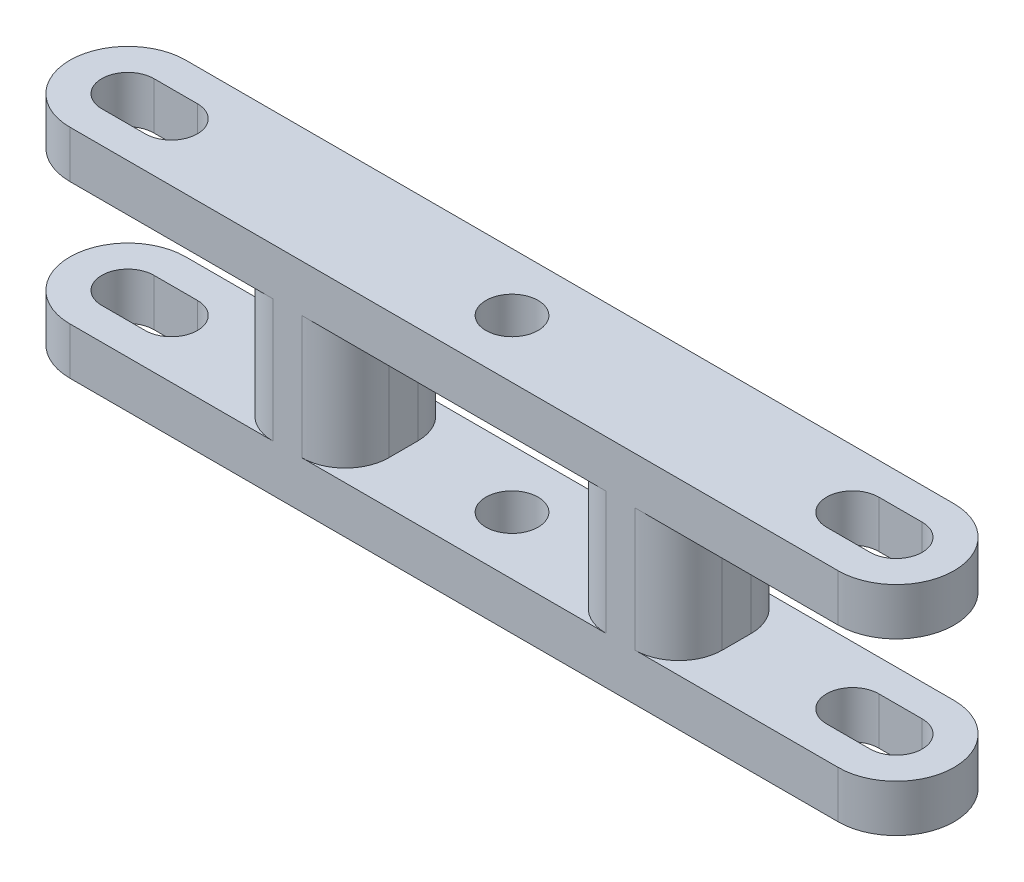
SolidWorks part; units mm, degrees
ref_plane "Front Plane" through (0, 0, 0) normal (0, 0, 1) x (1, 0, 0)
ref_plane "Top Plane" through (0, 0, 0) normal (0, 1, 0) x (1, 0, 0)
ref_plane "Right Plane" through (0, 0, 0) normal (1, 0, 0) x (0, 0, -1)
sketch "Sketch1" plane through (0, 0, 0) normal (0, 1, 0) x (1, 0, 0)
  line L0 (33.655, 0) -> (-33.655, 0) construction
  line L1 (-33.655, 0) -> (-29.845, 0) construction
  line L2 (33.655, -5.08) -> (-33.655, -5.08)
  line L3 (33.655, 5.08) -> (-33.655, 5.08)
  line L6 (33.655, 0) -> (29.845, 0) construction
  line L7 (33.655, -2.286) -> (29.845, -2.286)
  line L8 (33.655, 2.286) -> (29.845, 2.286)
  line L9 (-33.655, 2.286) -> (-29.845, 2.286)
  line L10 (-33.655, -2.286) -> (-29.845, -2.286)
  arc A0 (33.655, -5.08) -> (33.655, 5.08) centre (33.655, 0) ccw
  arc A1 (-33.655, 5.08) -> (-33.655, -5.08) centre (-33.655, 0) ccw
  arc A6 (33.655, -2.286) -> (33.655, 2.286) centre (33.655, 0) ccw
  arc A7 (29.845, 2.286) -> (29.845, -2.286) centre (29.845, 0) ccw
  circle A8 centre (0, 0) radius 2.286
  arc A9 (-33.655, 2.286) -> (-33.655, -2.286) centre (-33.655, 0) ccw
  arc A10 (-29.845, -2.286) -> (-29.845, 2.286) centre (-29.845, 0) ccw
  point P5 (0, 0)
  point P12 (-31.75, 0)
  point P19 (31.75, 0)
  dimension "D5" = 4.572
  dimension "D6" = 3.81
  dimension "D1" = 4.572
  dimension "D2" = 4.572
  dimension "D3" = 10.16
  dimension "D4" = 67.31
  dimension "D7" = 3.81
extrude "Boss-Extrude1" add sketch "Sketch1" along normal mid plane 19.05
sketch "Sketch3" plane through (0, 0, 5.08) normal (0, 0, 1) x (1, 0, 0)
  line L0 (-38.735, 9.525) -> (-38.735, -9.525) construction
  line L1 (-38.735, 5.3975) -> (-19.685, 5.3975)
  line L2 (-38.735, 5.3975) -> (-38.735, -5.3975)
  line L3 (-38.735, -5.3975) -> (-19.685, -5.3975)
  line L4 (-19.685, 5.3975) -> (-19.685, -5.3975)
  line L5 (0, 9.525) -> (0, -9.525) construction
  line L6 (9.525, -5.3975) -> (-9.525, -5.3975)
  line L7 (9.525, -5.3975) -> (9.525, 5.3975)
  line L8 (9.525, 5.3975) -> (-9.525, 5.3975)
  line L9 (-9.525, -5.3975) -> (-9.525, 5.3975)
  line L10 (9.525, -5.3975) -> (-9.525, 5.3975) construction
  line L11 (9.525, 5.3975) -> (-9.525, -5.3975) construction
  line L12 (-33.655, 9.525) -> (33.655, 9.525) construction
  line L13 (-33.655, -9.525) -> (33.655, -9.525) construction
  line L14 (19.685, 5.3975) -> (19.685, -5.3975)
  line L15 (38.735, -5.3975) -> (19.685, -5.3975)
  line L16 (38.735, 5.3975) -> (38.735, -5.3975)
  line L17 (38.735, 5.3975) -> (19.685, 5.3975)
  point P4 (-38.735, 0)
  point P9 (0, 0)
  point P19 (38.735, 0)
  dimension "D1" = 19.05
  dimension "D2" = 10.795
  dimension "D3" = 19.05
extrude "Cut-Extrude1" cut sketch "Sketch3" against normal through all
fillet "Fillet1" radius 3.81 8 edges at (19.685, 0, -5.08) (19.685, 0, 5.08) (9.525, 0, -5.08) (9.525, 0, 5.08) (-9.525, 0, -5.08) (-9.525, 0, 5.08) (-19.685, 0, 5.08) (-19.685, 0, -5.08)
